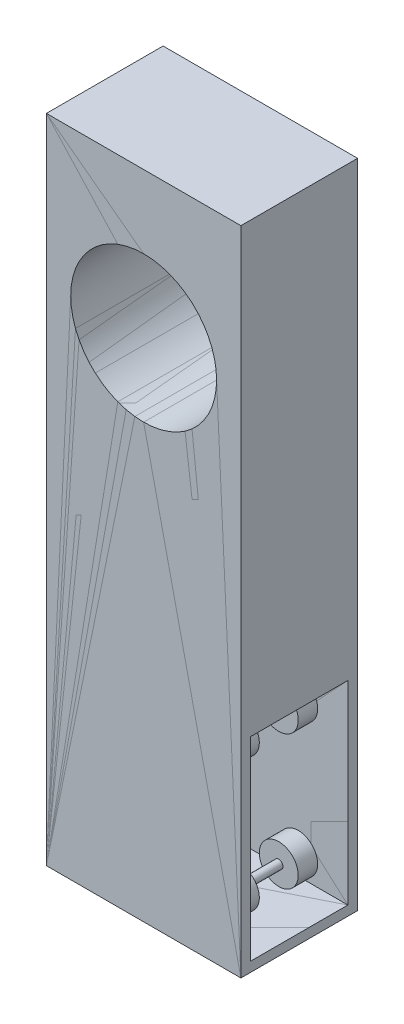
SolidWorks part; units mm, degrees
ref_plane "Front Plane" through (0, 0, 0) normal (0, 0, 1) x (1, 0, 0)
ref_plane "Top Plane" through (0, 0, 0) normal (0, 1, 0) x (1, 0, 0)
ref_plane "Right Plane" through (0, 0, 0) normal (1, 0, 0) x (0, 0, -1)
sketch "Sketch1" plane through (0, 0, 0) normal (1, 0, 0) x (0, 0, -1)
  line L1 (-12.7, -25.4) -> (12.7, -25.4)
  line L2 (-12.7, -25.4) -> (-12.7, 25.4)
  line L3 (-12.7, 25.4) -> (12.7, 25.4)
  line L4 (12.7, -25.4) -> (12.7, 25.4)
  line L5 (-12.7, -25.4) -> (12.7, 25.4) construction
  line L6 (-12.7, 25.4) -> (12.7, -25.4) construction
  line L7 (-15.24, -27.94) -> (15.24, -27.94)
  line L8 (-15.24, -27.94) -> (-15.24, 27.94)
  line L9 (-15.24, 27.94) -> (15.24, 27.94)
  line L10 (15.24, -27.94) -> (15.24, 27.94)
  line L11 (-15.24, -27.94) -> (15.24, 27.94) construction
  line L12 (-15.24, 27.94) -> (15.24, -27.94) construction
  point P0 (0, 0)
  point P6 (0, 0)
  dimension "D1" = 25.4
  dimension "D2" = 50.8
  dimension "D3" = 30.48
  dimension "D4" = 55.88
extrude "Boss-Extrude1" add sketch "Sketch1" along normal blind 50.8
ref_plane "Plane1" through (25.4, 0, 0) normal (1, 0, 0) x (0, 0, -1)
ref_plane "Plane2" through (0, 0, -7.62) normal (0, 0, 1) x (1, 0, 0)
sketch "Sketch6" plane through (0, 0, -7.62) normal (0, 0, 1) x (1, 0, 0)
  circle A0 centre (10.4304, 17.5442) radius 5.08
  circle A1 centre (10.4304, 17.5442) radius 1.1017
  point P3 (10.4304, 17.5442)
  dimension "D1" = 10.16
extrude "Boss-Extrude2" add sketch "Sketch6" along normal mid plane 5.08 separate body
ref_plane "Plane3" through (0, 0, 0) normal (0, 0, 1) x (1, 0, 0)
mirror "Mirror6" about plane through (0, 0, 0) normal (0, 0, 1) of bodies 102
ref_plane "Plane4" through (0, 0, 0) normal (0, -1, 0) x (-1, 0, 0)
mirror "Mirror7" about plane through (0, 0, 0) normal (0, -1, 0) of bodies 102 103
sketch "Sketch7" plane through (0, 0, -12.7) normal (0, 0, 1) x (1, 0, 0)
  circle A0 centre (10.4304, 17.5442) radius 1.1017 construction
  circle A1 centre (10.4304, 17.5442) radius 1.1017
extrude "Boss-Extrude3" add sketch "Sketch7" along normal up to surface (25.4 mm away) up to face at (25.4, 0, 12.7)
mirror "Mirror8" about plane through (0, 0, 0) normal (0, -1, 0) of bodies 106
sketch "Sketch8" plane through (0, 27.94, 0) normal (0, 1, 0) x (1, 0, 0)
  line L4 (0, 15.24) -> (0, -15.24)
  line L5 (0, -15.24) -> (50.8, -15.24)
  line L6 (50.8, -15.24) -> (50.8, 15.24)
  line L7 (50.8, 15.24) -> (0, 15.24)
  line L8 (0, 15.24) -> (0, -15.24)
  line L9 (0, -15.24) -> (50.8, -15.24)
  line L10 (50.8, -15.24) -> (50.8, 15.24)
  line L11 (50.8, 15.24) -> (0, 15.24)
  dimension "D1" = 0
extrude "Boss-Extrude4" add sketch "Sketch8" along normal blind 114.3
ref_plane "Plane5" through (25.4, 0, 0) normal (1, 0, 0) x (0, 0, -1)
mirror "Mirror10" about plane through (25.4, 0, 0) normal (1, 0, 0) of bodies 108
sketch "Sketch9" plane through (0, 0, 15.24) normal (0, 0, 1) x (1, 0, 0)
  line L0 (25.4, 142.24) -> (25.4, -27.94) construction
  line L1 (50.8, 142.24) -> (0, 142.24) construction
  line L2 (0, -27.94) -> (50.8, -27.94) construction
  circle A0 centre (25.4, 104.14) radius 19.05
  point P2 (0, 0)
  point P9 (25.4, 96.5681)
  point P10 (25.4, 101.3279)
  dimension "D1" = 38.1
  dimension "D2" = 38.1
extrude "Cut-Extrude1" cut sketch "Sketch9" against normal through all
sketch "Sketch10" plane through (0, 0, 15.24) normal (0, 0, 1) x (1, 0, 0)
  line L4 (0, -27.94) -> (50.8, -27.94)
  line L5 (50.8, -27.94) -> (50.8, 142.24)
  line L6 (50.8, 142.24) -> (0, 142.24)
  line L7 (0, 142.24) -> (0, -27.94)
  line L8 (0, -27.94) -> (50.8, -27.94)
  line L9 (50.8, -27.94) -> (50.8, 142.24)
  line L10 (50.8, 142.24) -> (0, 142.24)
  line L11 (0, 142.24) -> (0, -27.94)
  circle A0 centre (10.4304, -17.5442) radius 5.08 construction
  circle A1 centre (10.4304, -17.5442) radius 5.08
  dimension "D1" = 0
